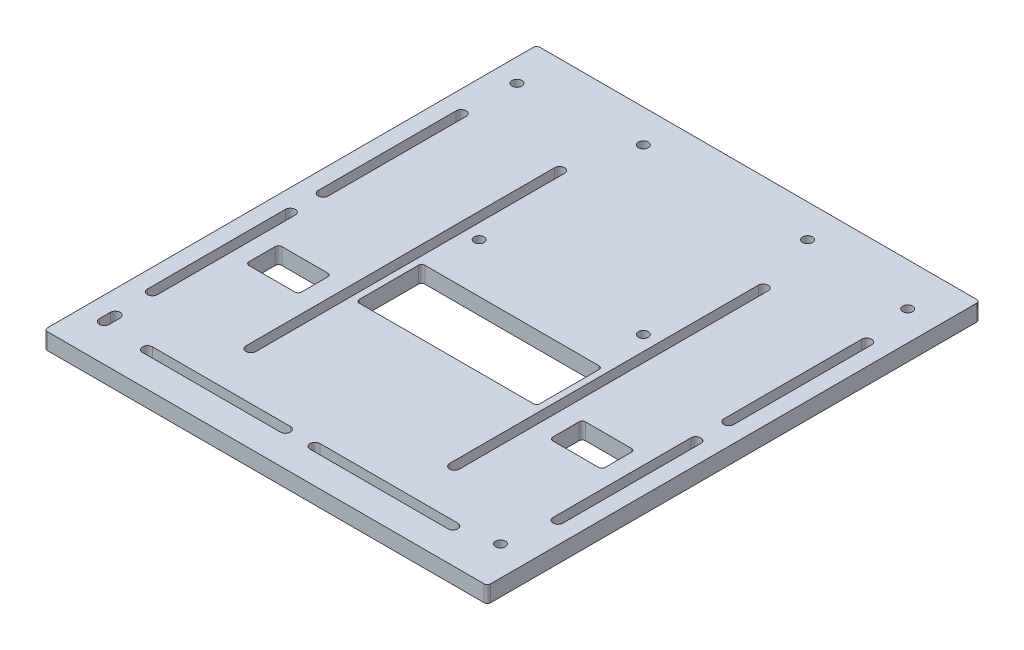
SolidWorks part; units mm, degrees
ref_plane "Front Plane" through (0, 0, 0) normal (0, 0, 1) x (1, 0, 0)
ref_plane "Top Plane" through (0, 0, 0) normal (0, 1, 0) x (1, 0, 0)
ref_plane "Right Plane" through (0, 0, 0) normal (1, 0, 0) x (0, 0, -1)
sketch "Sketch1" plane through (0, 0, 0) normal (0, 1, 0) x (1, 0, 0)
  line L1 (-4.8598, 4.4139) -> (128.1402, 4.4139)
  line L2 (-5.8598, 3.4139) -> (-5.8598, -144.5861)
  line L3 (-4.8598, -145.5861) -> (128.1402, -145.5861)
  line L4 (129.1402, 3.4139) -> (129.1402, -144.5861)
  arc A0 (-5.8598, -144.5861) -> (-4.8598, -145.5861) centre (-4.8598, -144.5861) ccw
  arc A1 (128.1402, -145.5861) -> (129.1402, -144.5861) centre (128.1402, -144.5861) ccw
  arc A2 (128.1402, 4.4139) -> (129.1402, 3.4139) centre (128.1402, 3.4139) cw
  arc A3 (-4.8598, 4.4139) -> (-5.8598, 3.4139) centre (-4.8598, 3.4139) ccw
  point P6 (-5.8598, -145.5861)
  point P11 (129.1402, 4.4139)
  point P14 (-5.8598, 4.4139)
  dimension "D3" = 1
  dimension "D1" = 150
  dimension "D2" = 135
extrude "Boss-Extrude1" add sketch "Sketch1" along normal blind 5
sketch "Sketch3" plane through (75.2045, 5, 34.1966) normal (0, 1, 0) x (1, 0, 0)
  line L0 (47.4357, -83.3895) -> (47.4357, -41.3895) construction
  line L1 (45.9357, -83.3895) -> (45.9357, -41.3895)
  line L2 (48.9357, -83.3895) -> (48.9357, -41.3895)
  line L3 (52.9357, 38.6105) -> (-80.0643, 38.6105) construction
  line L5 (47.4357, -31.3895) -> (47.4357, 10.6105) construction
  line L8 (45.9357, -31.3895) -> (45.9357, 10.6105)
  line L9 (-81.0643, 37.6105) -> (-81.0643, -110.3895) construction
  line L10 (48.9357, -31.3895) -> (48.9357, 10.6105)
  line L13 (-74.5643, -84.8895) -> (-74.5643, -42.8895) construction
  line L14 (-73.0643, -84.8895) -> (-73.0643, -42.8895)
  line L15 (-76.0643, -84.8895) -> (-76.0643, -42.8895)
  line L16 (-74.5643, -32.8895) -> (-74.5643, 9.1105) construction
  line L17 (-73.0643, -32.8895) -> (-73.0643, 9.1105)
  line L18 (-76.0643, -32.8895) -> (-76.0643, 9.1105)
  arc A0 (45.9357, -83.3895) -> (48.9357, -83.3895) centre (47.4357, -83.3895) ccw
  arc A1 (48.9357, -41.3895) -> (45.9357, -41.3895) centre (47.4357, -41.3895) ccw
  arc A8 (45.9357, -31.3895) -> (48.9357, -31.3895) centre (47.4357, -31.3895) ccw
  arc A9 (48.9357, 10.6105) -> (45.9357, 10.6105) centre (47.4357, 10.6105) ccw
  arc A10 (-73.0643, -84.8895) -> (-76.0643, -84.8895) centre (-74.5643, -84.8895) cw
  arc A11 (-76.0643, -42.8895) -> (-73.0643, -42.8895) centre (-74.5643, -42.8895) cw
  arc A12 (-73.0643, -32.8895) -> (-76.0643, -32.8895) centre (-74.5643, -32.8895) cw
  arc A13 (-76.0643, 9.1105) -> (-73.0643, 9.1105) centre (-74.5643, 9.1105) cw
  point P2 (47.4357, -62.3895)
  point P9 (47.4357, -84.8895)
  point P10 (0, 0)
  point P11 (-74.5643, 10.6105)
  point P14 (47.4357, -10.3895)
  point P19 (47.4357, -32.8895)
  point P20 (47.4357, -39.8895)
  point P21 (47.4357, 12.1105)
  point P22 (-80.0886, -29.128)
  point P28 (-74.5643, -63.8895)
  point P35 (-74.5643, -11.8895)
  dimension "D1" = 3
  dimension "D2" = 45
  dimension "D3" = 5
  dimension "D4" = 3
  dimension "D5" = 7
  dimension "D6" = 45
  dimension "D7" = 3
  dimension "D8" = 5
  dimension "D9" = 28
  dimension "D10" = 42
  dimension "D11" = 10
  dimension "D12" = 42
  dimension "D13" = 10
  dimension "D14" = 10
  dimension "D15" = 10
  dimension "D16" = 28
extrude "Cut-Extrude1" cut sketch "Sketch3" against normal blind 5
sketch "Sketch5" plane through (75.2045, 5, 34.1966) normal (0, 1, 0) x (1, 0, 0)
  line L0 (-60.0643, -100.8895) -> (-18.0643, -100.8895) construction
  line L1 (-60.0643, -99.3895) -> (-18.0643, -99.3895)
  line L2 (-60.0643, -102.3895) -> (-18.0643, -102.3895)
  line L4 (-81.0643, 37.6105) -> (-81.0643, -110.3895) construction
  line L5 (-9.0643, -100.8895) -> (32.9357, -100.8895) construction
  line L6 (-9.0643, -99.3895) -> (32.9357, -99.3895)
  line L7 (-9.0643, -102.3895) -> (32.9357, -102.3895)
  line L9 (52.9357, 38.6105) -> (-80.0643, 38.6105) construction
  arc A0 (-60.0643, -99.3895) -> (-60.0643, -102.3895) centre (-60.0643, -100.8895) ccw
  arc A1 (-18.0643, -102.3895) -> (-18.0643, -99.3895) centre (-18.0643, -100.8895) ccw
  arc A2 (-9.0643, -99.3895) -> (-9.0643, -102.3895) centre (-9.0643, -100.8895) ccw
  arc A3 (32.9357, -102.3895) -> (32.9357, -99.3895) centre (32.9357, -100.8895) ccw
  point P2 (-39.0643, -100.8895)
  point P7 (-61.5643, -100.8895)
  point P14 (11.9357, -100.8895)
  dimension "D1" = 3
  dimension "D2" = 42
  dimension "D3" = 9
  dimension "D4" = 9
  dimension "D5" = 3
  dimension "D6" = 19.5
  dimension "D7" = 42
  dimension "D8" = 138
extrude "Cut-Extrude2" cut sketch "Sketch5" against normal blind 5
sketch "Sketch7" plane through (75.2045, 5, 34.1966) normal (0, 1, 0) x (1, 0, 0)
  line L8 (52.9357, 38.6105) -> (-80.0643, 38.6105) construction
  circle B0 centre (44.9357, -98.3895) radius 1.5
  circle B1 centre (44.9357, 25.6105) radius 1.5
  circle B2 centre (-74.0643, 25.6105) radius 1.5
  line B3 (-72.5643, -96.7125) -> (-72.5643, -100.0665)
  arc B4 (-75.5643, -100.0665) -> (-72.5643, -100.0665) centre (-74.0643, -100.0665) ccw
  line B5 (-75.5643, -96.7125) -> (-75.5643, -100.0665)
  arc B6 (-72.5643, -96.7125) -> (-75.5643, -96.7125) centre (-74.0643, -96.7125) ccw
  dimension "D1" = 13
sketch_block_instance "Block2-1"
sketch_block "Block2" parameters "D1"=3
extrude "Cut-Extrude3" cut sketch "Sketch7" against normal blind 5
sketch "Sketch9" plane through (75.2045, 5, 34.1966) normal (0, 1, 0) x (1, 0, 0)
  line L0 (53.9357, -110.3895) -> (53.9357, 37.6105) construction
  line L1 (-40.0643, -36.3895) -> (12.9357, -36.3895)
  line L2 (-41.0643, -37.3895) -> (-41.0643, -55.3895)
  line L3 (-40.0643, -56.3895) -> (12.9357, -56.3895)
  line L4 (13.9357, -37.3895) -> (13.9357, -55.3895)
  line L6 (52.9357, 38.6105) -> (-80.0643, 38.6105) construction
  arc A0 (-41.0643, -55.3895) -> (-40.0643, -56.3895) centre (-40.0643, -55.3895) ccw
  arc A1 (12.9357, -56.3895) -> (13.9357, -55.3895) centre (12.9357, -55.3895) ccw
  arc A2 (12.9357, -36.3895) -> (13.9357, -37.3895) centre (12.9357, -37.3895) cw
  arc A3 (-40.0643, -36.3895) -> (-41.0643, -37.3895) centre (-40.0643, -37.3895) ccw
  point P11 (13.9357, -56.3895)
  point P15 (13.9357, -36.3895)
  point P18 (-41.0643, -36.3895)
  dimension "D1" = 1
  dimension "D2" = 20
  dimension "D3" = 55
  dimension "D4" = 40
  dimension "D5" = 75
extrude "Cut-Extrude4" cut sketch "Sketch9" against normal blind 5
sketch "Sketch10" plane through (0, 5, 0) normal (0, 1, 0) x (1, 0, 0)
  line L1 (128.1402, 4.4139) -> (-4.8598, 4.4139) construction
  circle A0 centre (36.6402, -5.5861) radius 1.5
  circle A1 centre (86.6402, -5.5861) radius 1.5
  circle A2 centre (86.6402, -55.5861) radius 1.5
  circle A3 centre (36.6402, -55.5861) radius 1.5
  dimension "D1" = 50
  dimension "D2" = 50
  dimension "D4" = 10
extrude "Cut-Extrude5" cut sketch "Sketch10" against normal blind 5
sketch "Sketch11" plane through (0, 5, 0) normal (0, 1, 0) x (1, 0, 0)
  line L0 (30.6402, -25.0861) -> (30.6402, -119.0861) construction
  line L1 (32.1402, -25.0861) -> (32.1402, -119.0861)
  line L2 (29.1402, -25.0861) -> (29.1402, -119.0861)
  line L3 (-5.8598, 3.4139) -> (-5.8598, -144.5861) construction
  line L6 (92.6402, -25.0861) -> (92.6402, -119.0861) construction
  line L7 (91.1402, -25.0861) -> (91.1402, -119.0861)
  line L8 (94.1402, -25.0861) -> (94.1402, -119.0861)
  arc A0 (32.1402, -25.0861) -> (29.1402, -25.0861) centre (30.6402, -25.0861) ccw
  arc A1 (29.1402, -119.0861) -> (32.1402, -119.0861) centre (30.6402, -119.0861) ccw
  arc A2 (-0.8598, -119.0861) -> (2.1402, -119.0861) centre (0.6402, -119.0861) ccw construction
  arc A3 (91.1402, -25.0861) -> (94.1402, -25.0861) centre (92.6402, -25.0861) cw
  arc A4 (94.1402, -119.0861) -> (91.1402, -119.0861) centre (92.6402, -119.0861) cw
  point P2 (30.6402, -72.0861)
  point P10 (0.6402, -120.5861)
  point P13 (30.6402, -120.5861)
  point P16 (30.6402, -23.5861)
  point P21 (92.6402, -72.0861)
  dimension "D1" = 3
  dimension "D2" = 94
  dimension "D3" = 35
extrude "Cut-Extrude6" cut sketch "Sketch11" against normal blind 5
sketch "Sketch12" plane through (0, 5, 0) normal (0, 1, 0) x (1, 0, 0)
  line L1 (22.3946, -97.4409) -> (8.3946, -97.4409)
  line L2 (23.3946, -96.4409) -> (23.3946, -88.4409)
  line L3 (22.3946, -87.4409) -> (8.3946, -87.4409)
  line L4 (7.3946, -96.4409) -> (7.3946, -88.4409)
  line L7 (100.8859, -87.4409) -> (114.8859, -87.4409)
  line L8 (115.8859, -96.4409) -> (115.8859, -88.4409)
  line L9 (100.8859, -97.4409) -> (114.8859, -97.4409)
  line L10 (99.8859, -96.4409) -> (99.8859, -88.4409)
  arc A0 (22.3946, -87.4409) -> (23.3946, -88.4409) centre (22.3946, -88.4409) cw
  arc A1 (22.3946, -97.4409) -> (23.3946, -96.4409) centre (22.3946, -96.4409) ccw
  arc A2 (8.3946, -97.4409) -> (7.3946, -96.4409) centre (8.3946, -96.4409) cw
  arc A3 (8.3946, -87.4409) -> (7.3946, -88.4409) centre (8.3946, -88.4409) ccw
  arc A4 (114.8859, -87.4409) -> (115.8859, -88.4409) centre (114.8859, -88.4409) cw
  arc A5 (114.8859, -97.4409) -> (115.8859, -96.4409) centre (114.8859, -96.4409) ccw
  arc A6 (100.8859, -87.4409) -> (99.8859, -88.4409) centre (100.8859, -88.4409) ccw
  arc A7 (100.8859, -97.4409) -> (99.8859, -96.4409) centre (100.8859, -96.4409) cw
  point P12 (23.3946, -87.4409)
  point P15 (23.3946, -97.4409)
  point P20 (7.3946, -87.4409)
  dimension "D3" = 1
  dimension "D1" = 16
  dimension "D2" = 10
extrude "Cut-Extrude7" cut sketch "Sketch12" against normal blind 5
